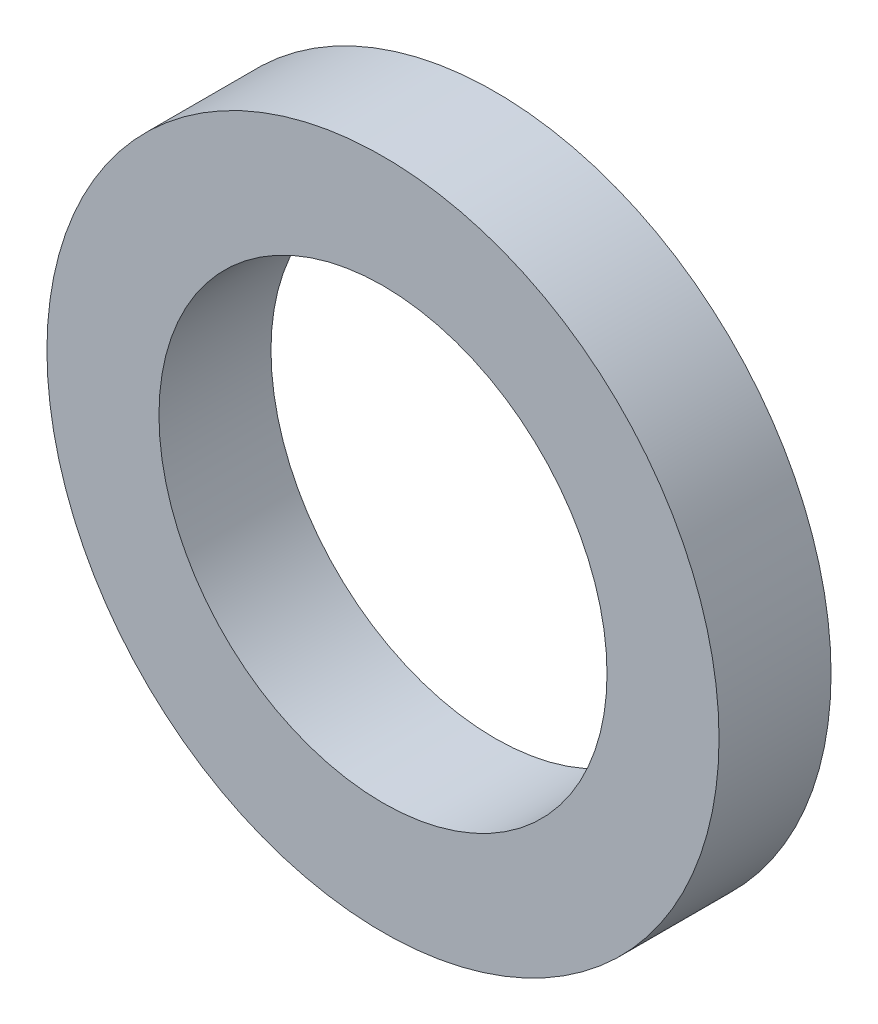
SolidWorks part; units mm, degrees
ref_plane "前视基准面" through (0, 0, 0) normal (0, 0, 1) x (1, 0, 0)
ref_plane "上视基准面" through (0, 0, 0) normal (0, 1, 0) x (1, 0, 0)
ref_plane "右视基准面" through (0, 0, 0) normal (1, 0, 0) x (0, 0, -1)
sketch "草图2" plane through (0, 0, 0) normal (0, 0, 1) x (1, 0, 0)
  circle A0 centre (0, 0) radius 15
  dimension "D1" = 30
extrude "凸台-拉伸1" add sketch "草图2" along normal blind 5
sketch "草图3" plane through (0, 0, 5) normal (0, 0, 1) x (1, 0, 0)
  circle A0 centre (0, 0) radius 10
  dimension "D1" = 20
extrude "切除-拉伸1" cut sketch "草图3" against normal blind 20
